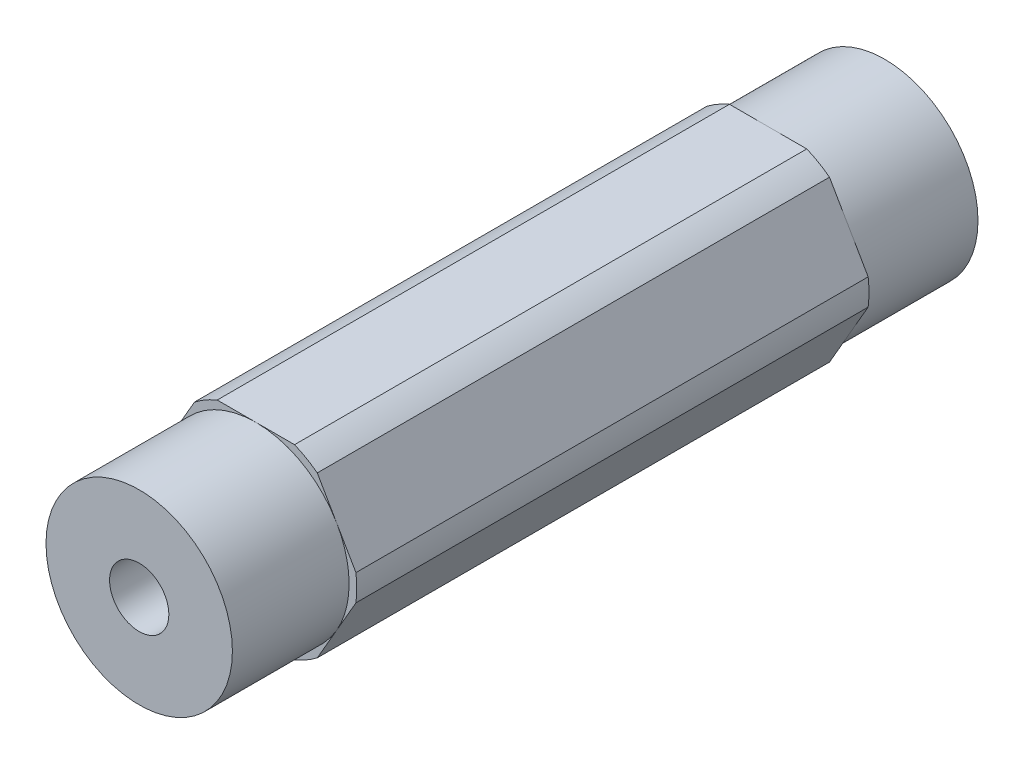
SolidWorks part; units mm, degrees
ref_plane "Front Plane" through (0, 0, 0) normal (0, 0, 1) x (1, 0, 0)
ref_plane "Top Plane" through (0, 0, 0) normal (0, 1, 0) x (1, 0, 0)
ref_plane "Right Plane" through (0, 0, 0) normal (1, 0, 0) x (0, 0, -1)
sketch "Sketch1" plane through (0, 0, 0) normal (0, 0, 1) x (1, 0, 0)
  line L1 (7.3323, 0) -> (3.6662, 6.35)
  line L2 (3.6662, 6.35) -> (-3.6662, 6.35)
  line L3 (-3.6662, 6.35) -> (-7.3323, 0)
  line L4 (-7.3323, 0) -> (-3.6662, -6.35)
  line L5 (-3.6662, -6.35) -> (3.6662, -6.35)
  line L6 (3.6662, -6.35) -> (7.3323, 0)
  circle A1 centre (0, 0) radius 6.35 construction
  dimension "D1" = 12.7
extrude "Boss-Extrude1" add sketch "Sketch1" along normal mid plane 50.8 contours L3 L4 L5 L6 L1 L2
sketch "Sketch2" plane through (0, 0, 25.4) normal (0, 0, 1) x (1, 0, 0)
  circle A0 centre (0, 0) radius 6.35
extrude "Cut-Extrude2" cut sketch "Sketch2" against normal blind 7.9502 flip side to cut
sketch "Sketch3" plane through (0, 0, 25.4) normal (0, 0, 1) x (1, 0, 0)
  circle A0 centre (0, 0) radius 6.875
  dimension "D1" = 13.75
extrude "Cut-Extrude4" cut sketch "Sketch3" against normal through all flip side to cut
mirror "Mirror1" about plane through (0, 0, 0) normal (0, 0, 1) of "Cut-Extrude2"
sketch "Sketch4" plane through (0, 0, 25.4) normal (0, 0, 1) x (1, 0, 0)
  circle A0 centre (0, 0) radius 2.0193
  dimension "D1" = 4.0386
extrude "Cut-Extrude5" cut sketch "Sketch4" against normal through all
